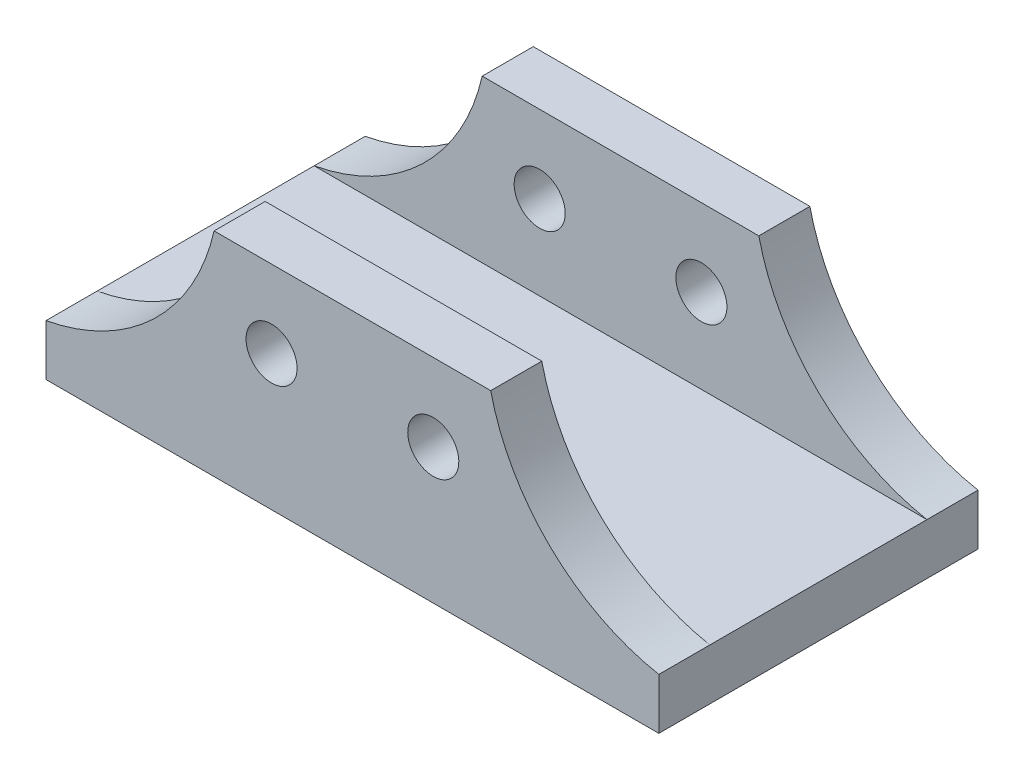
SolidWorks part; units mm, degrees
ref_plane "Front Plane" through (0, 0, 0) normal (0, 0, 1) x (1, 0, 0)
ref_plane "Top Plane" through (0, 0, 0) normal (0, 1, 0) x (1, 0, 0)
ref_plane "Right Plane" through (0, 0, 0) normal (1, 0, 0) x (0, 0, -1)
sketch "Sketch1" plane through (0, 0, 0) normal (0, 1, 0) x (1, 0, 0)
  line L1 (-72, 37.5) -> (72, 37.5)
  line L2 (-72, 37.5) -> (-72, -37.5)
  line L3 (-72, -37.5) -> (72, -37.5)
  line L4 (72, 37.5) -> (72, -37.5)
  line L5 (-72, 37.5) -> (72, -37.5) construction
  line L6 (-72, -37.5) -> (72, 37.5) construction
  point P0 (0, 0)
  dimension "D1" = 144
  dimension "D2" = 75
extrude "Boss-Extrude1" add sketch "Sketch1" along normal blind 12
sketch "Sketch2" plane through (0, 0, 37.5) normal (0, 0, 1) x (1, 0, 0)
  line L0 (-32.5, 50) -> (32.5, 50)
  line L1 (-72, 12) -> (72, 12)
  line L2 (0, 50) -> (0, 12) construction
  line L3 (-72, 0) -> (72, 0) construction
  line L4 (-72, 12) -> (-72, 0) construction
  arc A0 (-72, 12) -> (-32.5, 50) centre (-81.2436, 61.1381) ccw
  arc A1 (72, 12) -> (32.5, 50) centre (81.2436, 61.1381) cw
  circle A2 centre (-19, 31.7862) radius 6
  circle A4 centre (19, 31.7862) radius 6
  point P2 (0, 50)
  dimension "D3" = 50
  dimension "D4" = 53
  dimension "D5" = 19
  dimension "D6" = 12
  dimension "D1" = 50
  dimension "D2" = 65
extrude "Boss-Extrude2" add sketch "Sketch2" against normal up to surface (75 mm away) up to face at (0, 6, -37.5)
sketch "Sketch3" plane through (0, 0, 0) normal (1, 0, 0) x (0, 0, -1)
  line L0 (37.5, 50) -> (-37.5, 50) construction
  line L1 (-25.5, 50) -> (25.5, 50)
  line L2 (-25.5, 50) -> (-25.5, 12)
  line L3 (-25.5, 12) -> (25.5, 12)
  line L4 (25.5, 50) -> (25.5, 12)
  line L5 (-37.5, 12) -> (37.5, 12) construction
  line L6 (-37.5, 50) -> (-37.5, 12) construction
  line L7 (37.5, 12) -> (37.5, 50) construction
  dimension "D1" = 12
  dimension "D2" = 12
extrude "Cut-Extrude1" cut sketch "Sketch3" against normal mid plane 192
